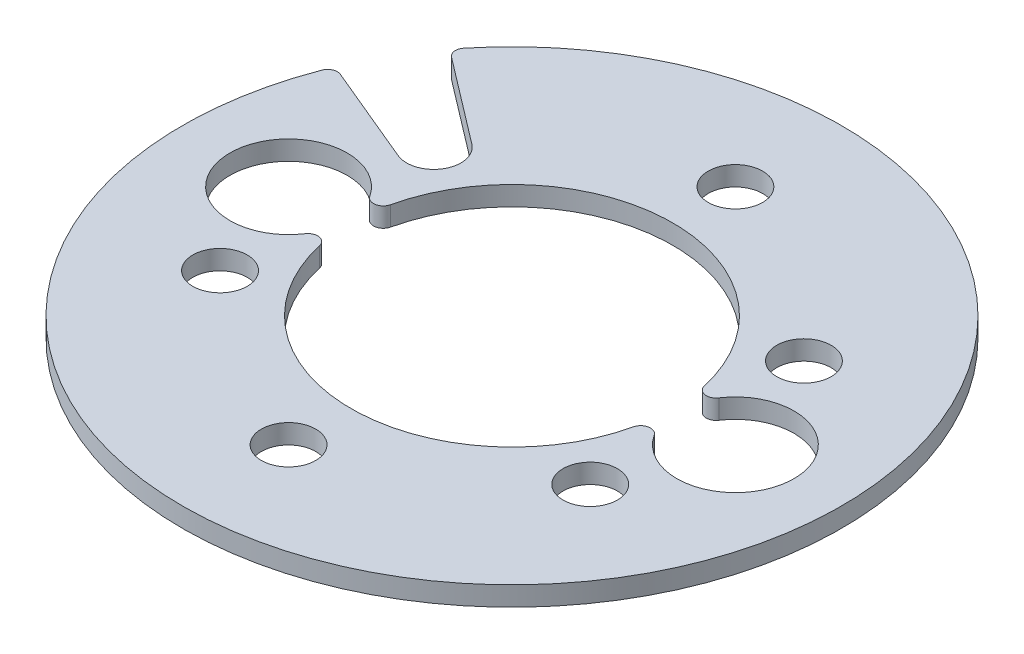
SolidWorks part; units mm, degrees
material "Polyethylene-UHMW Recycled"
ref_plane "Front Plane" through (0, 0, 0) normal (0, 0, 1) x (1, 0, 0)
ref_plane "Top Plane" through (0, 0, 0) normal (0, 1, 0) x (1, 0, 0)
ref_plane "Right Plane" through (0, 0, 0) normal (1, 0, 0) x (0, 0, -1)
sketch "Sketch1" plane through (0, 0, 0) normal (0, 1, 0) x (1, 0, 0)
  line L0 (0, 0) -> (0, 36.5125) construction
  line L1 (0, 0) -> (-30.2459, 17.4625) construction
  line L2 (0, 0) -> (17.4625, 30.2459) construction
  line L3 (0, 0) -> (30.2459, -17.4625) construction
  line L4 (0, 0) -> (-17.4625, -30.2459) construction
  line L5 (48.7364, 0) -> (53.848, 0) construction
  line L6 (-17.4625, 30.2459) -> (0, 0) construction
  line L7 (0, 0) -> (17.4625, -30.2459) construction
  line L8 (-30.2459, -17.4625) -> (0, 0) construction
  line L9 (0, 0) -> (30.2459, 17.4625) construction
  line L10 (0, 0) -> (36.5125, 0) construction
  line L11 (-27.5516, 20.9978) -> (-41.546, 31.6634)
  line L12 (-31.9604, 13.3615) -> (-48.1943, 20.1482)
  arc A0 (-50.2892, 19.2511) -> (-41.8165, 33.9262) centre (0, 0) ccw
  arc A1 (-25.6405, -5.8031) -> (25.6405, -5.8031) centre (0, 0) ccw
  circle A2 centre (0, 36.5125) radius 4.445
  circle A3 centre (0, -36.5125) radius 4.445
  circle A4 centre (0, 0) radius 36.5125 construction
  arc A5 (-28.5138, 5.2791) -> (-28.5138, -5.2791) centre (-36.5125, 0) ccw
  arc A6 (28.5138, -5.2791) -> (28.5138, 5.2791) centre (36.5125, 0) ccw
  circle A7 centre (0, 36.5125) radius 7.052 construction
  arc A8 (25.6405, 5.8031) -> (-25.6405, 5.8031) centre (0, 0) ccw
  circle A9 centre (0, 0) radius 62.0034 construction
  circle A10 centre (0, 0) radius 48.2249 construction
  circle A11 centre (30.2459, -17.4625) radius 6.8893 construction
  circle A12 centre (30.2459, -17.4625) radius 4.445
  circle A13 centre (17.4625, 30.2459) radius 4.445 construction
  arc A14 (-31.9604, 13.3615) -> (-27.5516, 20.9978) centre (-30.2459, 17.4625) ccw
  circle A15 centre (-17.4625, 30.2459) radius 4.445 construction
  circle A16 centre (17.4625, 30.2459) radius 6.5095 construction
  circle A17 centre (-17.4625, -30.2459) radius 4.445 construction
  circle A18 centre (17.4625, -30.2459) radius 4.445 construction
  circle A19 centre (30.2459, 17.4625) radius 4.445
  circle A20 centre (-30.2459, -17.4625) radius 4.445
  circle A21 centre (0, 0) radius 27.5571 construction
  arc A22 (25.6405, 5.8031) -> (28.5138, 5.2791) centre (27.1888, 6.1535) ccw
  arc A23 (25.6405, -5.8031) -> (28.5138, -5.2791) centre (27.1888, -6.1535) cw
  arc A24 (-28.5138, 5.2791) -> (-25.6405, 5.8031) centre (-27.1888, 6.1535) ccw
  arc A25 (-28.5138, -5.2791) -> (-25.6405, -5.8031) centre (-27.1888, -6.1535) cw
  circle A26 centre (-36.5125, 0) radius 9.5837 construction
  arc A27 (-50.2892, 19.2511) -> (-48.1943, 20.1482) centre (-48.8066, 18.6836) cw
  arc A28 (-41.546, 31.6634) -> (-41.8165, 33.9262) centre (-40.5837, 32.926) cw
  dimension "D1" = 107.696
  dimension "D2" = 73.025
  dimension "D6" = 9.5837
  dimension "D7" = 26.289
  dimension "D8" = 1.5875
  dimension "D11" = 8.89
  dimension "D12" = 8.89
  dimension "D3" = 69.85
  dimension "D4" = 30
  dimension "D5" = 60
  dimension "D9" = 30
  dimension "D10" = 60
extrude "Boss-Extrude1" add sketch "Sketch1" along normal blind 3.175
